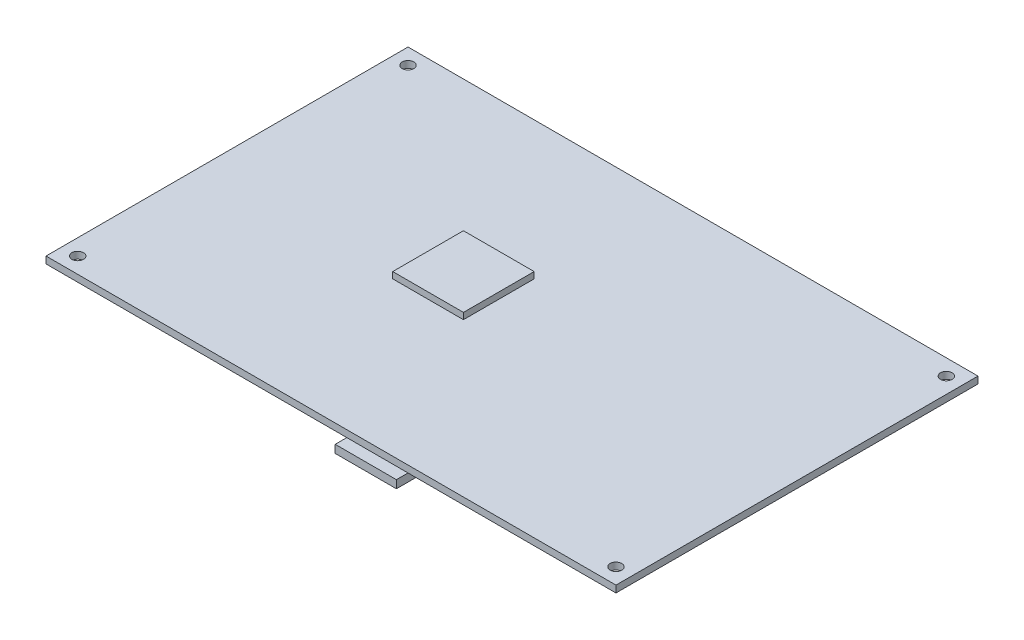
SolidWorks part; units mm, degrees
ref_plane "Front Plane" through (0, 0, 0) normal (0, 0, 1) x (1, 0, 0)
ref_plane "Top Plane" through (0, 0, 0) normal (0, 1, 0) x (1, 0, 0)
ref_plane "Right Plane" through (0, 0, 0) normal (1, 0, 0) x (0, 0, -1)
sketch "Sketch1" plane through (0, 0, 0) normal (0, 1, 0) x (1, 0, 0)
  line L1 (0, 0) -> (-137.16, 0)
  line L2 (0, 0) -> (0, 87.122)
  line L3 (0, 87.122) -> (-137.16, 87.122)
  line L4 (-137.16, 0) -> (-137.16, 87.122)
  circle A0 centre (-133.35, 83.312) radius 1.397
  circle A1 centre (-3.81, 3.81) radius 1.397
  circle A2 centre (-3.81, 83.312) radius 1.397
  circle A3 centre (-133.35, 3.81) radius 1.397
  dimension "D3" = 2.794
  dimension "D4" = 3.81
  dimension "D5" = 3.81
  dimension "D6" = 3.81
  dimension "D7" = 3.81
  dimension "D8" = 3.81
  dimension "D9" = 3.81
  dimension "D10" = 3.81
  dimension "D1" = 87.122
  dimension "D2" = 137.16
  dimension "D11" = 3.81
extrude "Boss-Extrude1" add sketch "Sketch1" along normal blind 1.651
sketch "Sketch2" plane through (0, 0, 0) normal (0, -1, 0) x (1, 0, 0)
  line L1 (-64.77, -11.7348) -> (-50.038, -11.7348)
  line L2 (-64.77, -11.7348) -> (-64.77, 2.794)
  line L3 (-64.77, 2.794) -> (-50.038, 2.794)
  line L4 (-50.038, -11.7348) -> (-50.038, 2.794)
  line L5 (-137.16, 0) -> (0, 0) construction
  line L6 (-137.16, -87.122) -> (-137.16, 0) construction
  dimension "D1" = 14.732
  dimension "D2" = 14.5288
  dimension "D3" = 2.794
  dimension "D4" = 72.39
extrude "Boss-Extrude2" add sketch "Sketch2" along normal blind 1.905
sketch "Sketch3" plane through (0, 1.651, 0) normal (0, 1, 0) x (1, 0, 0)
  line L0 (-137.16, 87.122) -> (-137.16, 0) construction
  line L1 (-90.678, 36.957) -> (-73.66, 36.957)
  line L2 (-90.678, 36.957) -> (-90.678, 53.975)
  line L3 (-90.678, 53.975) -> (-73.66, 53.975)
  line L4 (-73.66, 36.957) -> (-73.66, 53.975)
  line L5 (0, 87.122) -> (-137.16, 87.122) construction
  dimension "D1" = 17.018
  dimension "D2" = 17.018
  dimension "D3" = 63.5
  dimension "D4" = 50.165
extrude "Boss-Extrude3" add sketch "Sketch3" along normal blind 1.524
